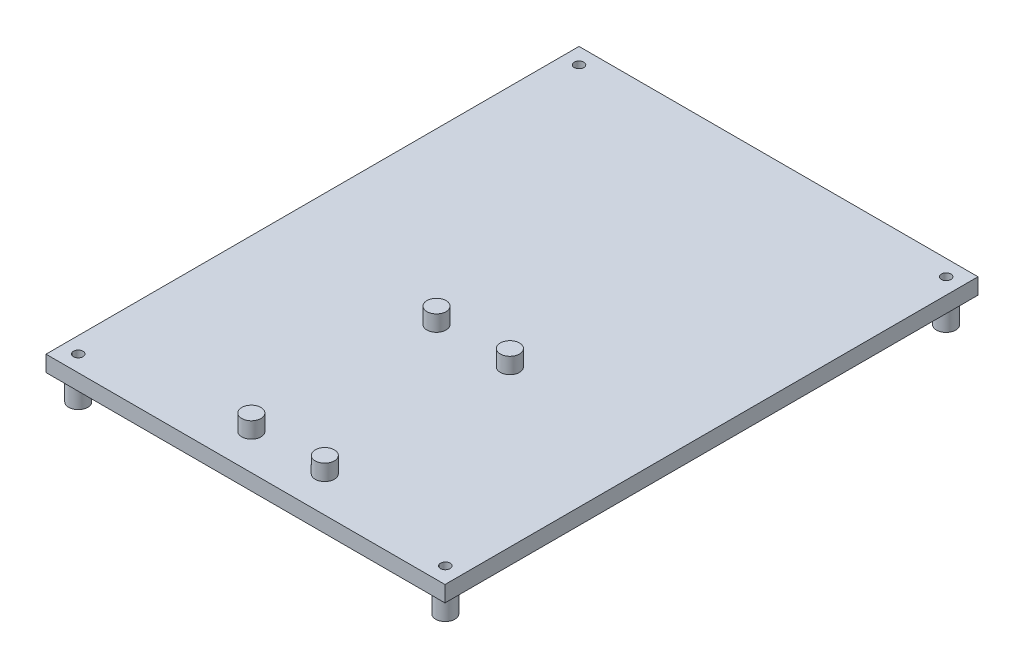
SolidWorks part; units mm, degrees
ref_plane "Plan de face" through (0, 0, 0) normal (0, 0, 1) x (1, 0, 0)
ref_plane "Plan de dessus" through (0, 0, 0) normal (0, 1, 0) x (1, 0, 0)
ref_plane "Plan de droite" through (0, 0, 0) normal (1, 0, 0) x (0, 0, -1)
sketch "Esquisse1" plane through (0, 0, 0) normal (0, 1, 0) x (1, 0, 0)
  line L1 (-62.5, -83.5) -> (62.5, -83.5)
  line L2 (-62.5, -83.5) -> (-62.5, 83.5)
  line L3 (-62.5, 83.5) -> (62.5, 83.5)
  line L4 (62.5, -83.5) -> (62.5, 83.5)
  line L5 (-62.5, -83.5) -> (62.5, 83.5) construction
  line L6 (-62.5, 83.5) -> (62.5, -83.5) construction
  point P0 (0, 0)
  dimension "D1" = 125
  dimension "D2" = 167
extrude "Boss.-Extru.1" add sketch "Esquisse1" along normal blind 5
sketch "Esquisse2" plane through (0, 0, 0) normal (0, -1, 0) x (1, 0, 0)
  circle A0 centre (-57.5, 78.4) radius 1.5
  circle A1 centre (57.5, 78.4) radius 1.5
  circle A2 centre (57.5, -78.5) radius 1.5
  circle A3 centre (-57.5, -78.5) radius 1.5
  point P8 (0, 0)
  point P9 (-53.8697, -80.294)
  point P10 (0, 0)
  point P11 (0, 0)
  point P12 (0, 0)
  point P13 (-134.3284, -74.1203)
  point P14 (0, 0)
  point P15 (-57.6302, -82.6423)
  dimension "D1" = 3
  dimension "D2" = 115
  dimension "D3" = 156.9
  dimension "D4" = 5
  dimension "D5" = 5
extrude "Enlèv. mat.-Extru.1" cut sketch "Esquisse2" along normal through all and the other way through all
sketch "Esquisse3" plane through (0, 0, 0) normal (0, -1, 0) x (1, 0, 0)
  circle A0 centre (-57.5, 78.4) radius 2.9922
  circle A1 centre (57.5, 78.4) radius 2.9922
  circle A2 centre (57.5, -78.5) radius 2.9922
  circle A3 centre (-57.5, -78.5) radius 2.9922
extrude "Boss.-Extru.2" add sketch "Esquisse3" along normal blind 8
sketch "Esquisse5" plane through (0, 5, 0) normal (0, 1, 0) x (1, 0, 0)
  circle A0 centre (-57.5, 78.5) radius 1.5
  circle A1 centre (57.5, 78.5) radius 1.5
  circle A2 centre (57.5, -78.4) radius 1.5
  circle A3 centre (-57.5, -78.4) radius 1.5
extrude "Enlèv. mat.-Extru.2" cut sketch "Esquisse5" against normal through all
sketch "Esquisse6" plane through (0, 5, 0) normal (0, 1, 0) x (1, 0, 0)
  circle A0 centre (-9.3684, -72.289) radius 3
  circle A1 centre (-9.3684, -14.289) radius 3
  circle A2 centre (13.6316, -14.289) radius 3
  circle A3 centre (13.6316, -72.289) radius 3
  point P8 (0, 0)
  point P9 (0, 0)
  point P10 (0, 0)
  point P11 (0, 0)
  dimension "D1" = 6
  dimension "D2" = 23
  dimension "D3" = 58
extrude "Boss.-Extru.3" add sketch "Esquisse6" along normal blind 5
